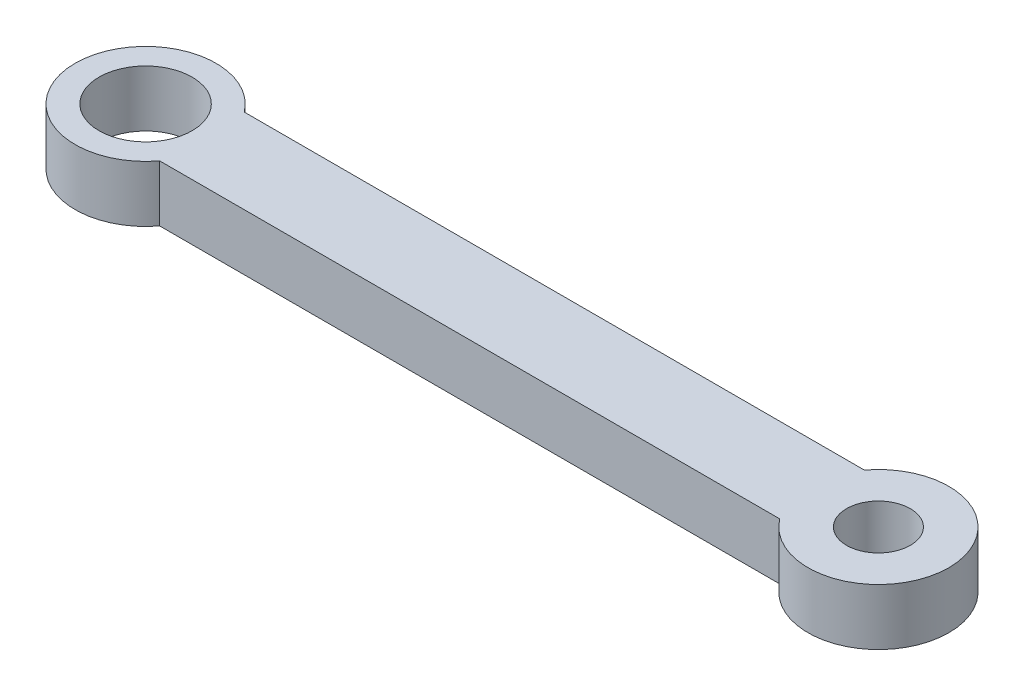
SolidWorks part; units mm, degrees
ref_plane "Front Plane" through (0, 0, 0) normal (0, 0, 1) x (1, 0, 0)
ref_plane "Top Plane" through (0, 0, 0) normal (0, 1, 0) x (1, 0, 0)
ref_plane "Right Plane" through (0, 0, 0) normal (1, 0, 0) x (0, 0, -1)
sketch "Sketch1" plane through (0, 0, 0) normal (0, 1, 0) x (1, 0, 0)
  line L0 (-11, 1.5) -> (11, 1.5)
  line L1 (-13, -1.5) -> (13, -1.5) construction
  line L2 (-13, -1.5) -> (-13, 1.5) construction
  line L3 (-13, 1.5) -> (13, 1.5) construction
  line L4 (13, -1.5) -> (13, 1.5) construction
  line L5 (-13, -1.5) -> (13, 1.5) construction
  line L6 (-13, 1.5) -> (13, -1.5) construction
  line L7 (-11, -1.5) -> (11, -1.5)
  circle A0 centre (-13, 0) radius 2.5 construction
  circle A1 centre (13, 0) radius 2.5 construction
  arc A2 (-11, 1.5) -> (-11, -1.5) centre (-13, 0) ccw
  arc A3 (11, 1.5) -> (11, -1.5) centre (13, 0) cw
  circle A4 centre (-13, 0) radius 1.65
  circle A5 centre (13, 0) radius 1.1303
  point P0 (0, 0)
  dimension "D3" = 5
  dimension "D4" = 3.3
  dimension "D5" = 2.2606
  dimension "D1" = 26
  dimension "D2" = 3
extrude "Boss-Extrude1" add sketch "Sketch1" along normal blind 2
